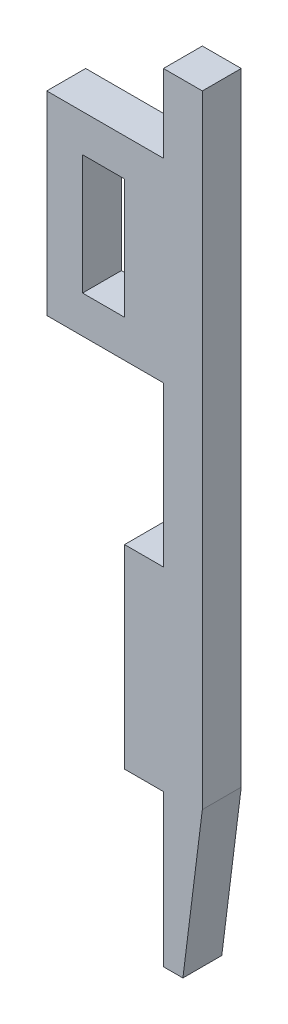
SolidWorks part; units mm, degrees
ref_plane "Front Plane" through (0, 0, 0) normal (0, 0, 1) x (1, 0, 0)
ref_plane "Top Plane" through (0, 0, 0) normal (0, 1, 0) x (1, 0, 0)
ref_plane "Right Plane" through (0, 0, 0) normal (1, 0, 0) x (0, 0, -1)
sketch "Sketch1" plane through (0, 0, 0) normal (0, 0, 1) x (1, 0, 0)
  line L0 (0, 0) -> (2.5, 0)
  line L1 (2.5, 0) -> (5, 20)
  line L2 (5, 20) -> (5, 100)
  line L3 (5, 100) -> (0, 100)
  line L4 (0, 100) -> (0, 90)
  line L5 (0, 90) -> (-15, 90)
  line L7 (-15, 65) -> (0, 65)
  line L8 (0, 44.5) -> (-15, 44.5)
  line L10 (-15, 19.5) -> (0, 19.5)
  line L11 (0, 65) -> (0, 44.5)
  line L12 (0, 19.5) -> (0, 0)
  line L13 (-15, 90) -> (-15, 65)
  line L14 (-15, 44.5) -> (-15, 19.5)
  line L16 (-10.4, 85.2) -> (-5, 85.2)
  line L17 (-10.4, 85.2) -> (-10.4, 69.8)
  line L18 (-10.4, 69.8) -> (-5, 69.8)
  line L19 (-5, 85.2) -> (-5, 69.8)
  line L20 (-10, 39.5) -> (-5, 39.5)
  line L21 (-10, 39.5) -> (-10, 24.5)
  line L22 (-10, 24.5) -> (-5, 24.5)
  line L23 (-5, 39.5) -> (-5, 24.5)
  point P12 (-7.5, 90)
  dimension "D1" = 2.5
  dimension "D2" = 100
  dimension "D3" = 5
  dimension "D4" = 20
  dimension "D5" = 25
  dimension "D6" = 25
  dimension "D7" = 10
  dimension "D8" = 20.5
  dimension "D9" = 20
  dimension "D10" = 20
  dimension "D11" = 5.4
  dimension "D12" = 15.4
  dimension "D13" = 4.8
  dimension "D14" = 4.6
  dimension "D15" = 15
  dimension "D16" = 5
  dimension "D17" = 5
  dimension "D18" = 5
extrude "Boss-Extrude1" add sketch "Sketch1" along normal blind 5
sketch "Sketch2" plane through (0, 0, 5) normal (0, 0, 1) x (1, 0, 0)
  line L0 (-15, 19.5) -> (0, 19.5) construction
  line L1 (-15, 44.5) -> (-5, 44.5)
  line L2 (-15, 44.5) -> (-15, 19.5)
  line L3 (-15, 19.5) -> (-5, 19.5)
  line L4 (-5, 44.5) -> (-5, 19.5)
  line L5 (-5, 24.5) -> (-5, 39.5) construction
extrude "Cut-Extrude1" cut sketch "Sketch2" against normal blind 10
move or copy body "Body-Move/Copy1" [suppressed] bodies to move or copy 101
